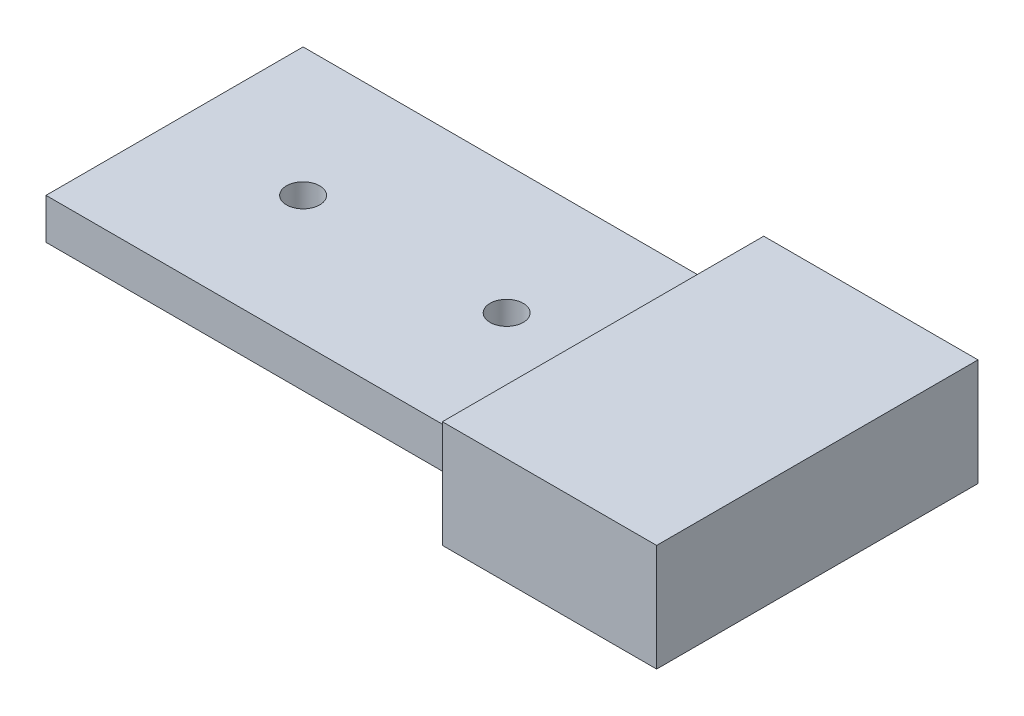
SolidWorks part; units mm, degrees
ref_plane "Front Plane" through (0, 0, 0) normal (0, 0, 1) x (1, 0, 0)
ref_plane "Top Plane" through (0, 0, 0) normal (0, 1, 0) x (1, 0, 0)
ref_plane "Right Plane" through (0, 0, 0) normal (1, 0, 0) x (0, 0, -1)
sketch "Sketch1" plane through (0, 0, 0) normal (1, 0, 0) x (0, 0, -1)
  line L1 (12, -1.9) -> (-12, -1.9)
  line L2 (12, -1.9) -> (12, 1.9)
  line L3 (12, 1.9) -> (-12, 1.9)
  line L4 (-12, -1.9) -> (-12, 1.9)
  line L5 (12, -1.9) -> (-12, 1.9) construction
  line L6 (12, 1.9) -> (-12, -1.9) construction
  point P0 (0, 0)
  dimension "D1" = 3.8
  dimension "D2" = 24
extrude "Boss-Extrude1" add sketch "Sketch1" along normal blind 40
sketch "Sketch2" plane through (0, -1.9, 0) normal (0, -1, 0) x (1, 0, 0)
  line L0 (0, 0) -> (12, 0) construction
  line L1 (12, 0) -> (31, 0) construction
  line L2 (31, 0) -> (43, 0) construction
  line L3 (40, 12) -> (40, -12) construction
  circle A0 centre (12, 0) radius 1.55
  circle A1 centre (31, 0) radius 1.55
  dimension "D3" = 3.1
  dimension "D4" = 3.1
  dimension "D1" = 3
  dimension "D2" = 19
extrude "Cut-Extrude1" cut sketch "Sketch2" against normal through all
sketch "Sketch3" plane through (40, 0, 0) normal (1, 0, 0) x (0, 0, -1)
  line L0 (-12, -1.9) -> (12, -1.9) construction
  line L1 (15, -4.9) -> (-15, -4.9)
  line L2 (15, -4.9) -> (15, 5.1)
  line L3 (15, 5.1) -> (-15, 5.1)
  line L4 (-15, -4.9) -> (-15, 5.1)
  line L5 (15, -4.9) -> (-15, 5.1) construction
  line L6 (15, 5.1) -> (-15, -4.9) construction
  point P0 (0, 0.1)
  dimension "D1" = 30
  dimension "D2" = 2
  dimension "D3" = 3
extrude "Boss-Extrude2" add sketch "Sketch3" along normal blind 20
sketch "Sketch5" plane through (0, 0, 0) normal (0, 0, 1) x (1, 0, 0)
  line L0 (102.7817, -25.3507) -> (102.7817, -34.4126)
  line L1 (102.7817, -34.4126) -> (105.7817, -34.4126)
  line L2 (105.7817, -34.4126) -> (105.7817, -23.9494)
  line L3 (60, -4.9) -> (60, 5.1)
  line L4 (60, 5.1) -> (40, 5.1) construction
  line L5 (60, -4.9) -> (40, -4.9) construction
  line L6 (84.4635, 1.8046) -> (60, -25.3507) construction
  line L7 (104.1839, -13.9555) -> (60, -25.3507) construction
  spline S0 degree 3 poles (60, -4.9) (64.6622, -4.9) (80.0858, -4.8031) (98.4976, -10.1923) (102.7817, -21.518) (102.7817, -25.3507) knots 0 0 0 0 0.341351 0.794372 1 1 1 1
  spline S1 degree 3 poles (105.7817, -23.9494) (105.7817, -19.6116) (104.4509, -9.4487) (84.8564, 4.4741) (67.7422, 5.1) (60, 5.1) knots 0 0 0 0 0.168541 0.588933 1 1 1 1
  dimension "D1" = 10
  dimension "D2" = 5
  dimension "D3" = 3
